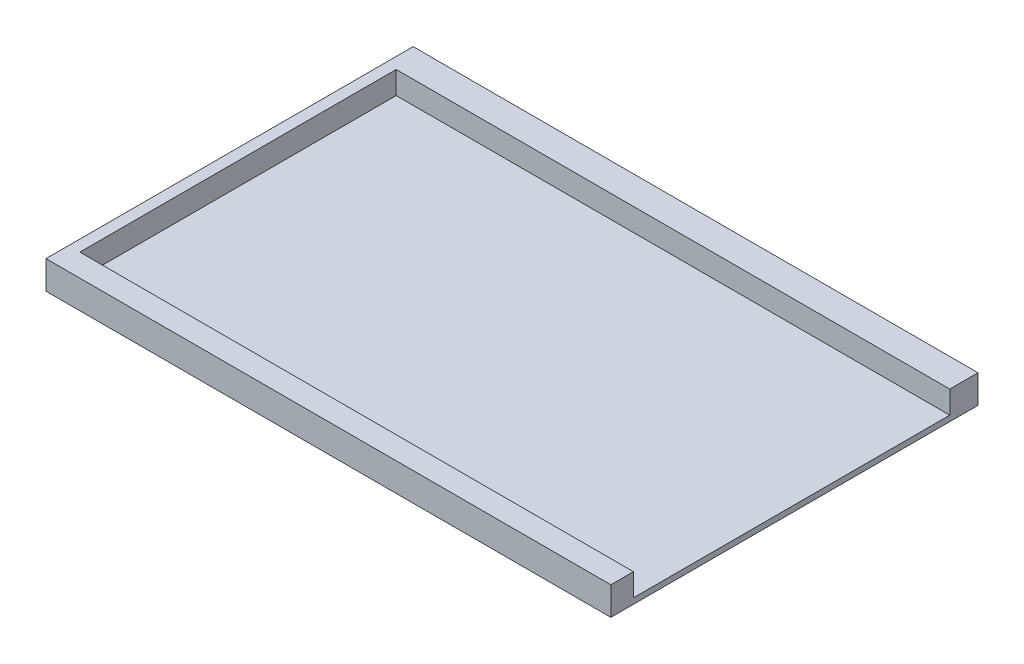
SolidWorks part; units mm, degrees
ref_plane "Front Plane" through (0, 0, 0) normal (0, 0, 1) x (1, 0, 0)
ref_plane "Top Plane" through (0, 0, 0) normal (0, 1, 0) x (1, 0, 0)
ref_plane "Right Plane" through (0, 0, 0) normal (1, 0, 0) x (0, 0, -1)
sketch "Sketch3" plane through (0, 0, 0) normal (0, 1, 0) x (1, 0, 0)
  line L1 (-50, -32.5) -> (50, -32.5)
  line L2 (-50, -32.5) -> (-50, 32.5)
  line L3 (-50, 32.5) -> (50, 32.5)
  line L4 (50, -32.5) -> (50, 32.5)
  line L5 (0, 32.5) -> (0, -32.5) construction
  line L6 (-50, 0) -> (50, 0) construction
  point P0 (0, 0)
  dimension "D1" = 100
  dimension "D2" = 65
extrude "Boss-Extrude2" add sketch "Sketch3" along normal blind 5
sketch "Sketch5" plane through (50, 0, 0) normal (1, 0, 0) x (0, 0, -1)
  line L0 (-32.5, 5) -> (32.5, 5) construction
  line L1 (-28.5, 1) -> (27.5, 1)
  line L2 (-28.5, 1) -> (-28.5, 5)
  line L3 (-28.5, 5) -> (27.5, 5)
  line L4 (27.5, 1) -> (27.5, 5)
  line L5 (-32.5, 0) -> (32.5, 0) construction
  line L6 (-32.5, 5) -> (-32.5, 0) construction
  line L7 (32.5, 5) -> (32.5, 0) construction
  dimension "D1" = 1
  dimension "D2" = 4
  dimension "D3" = 5
extrude "Cut-Extrude1" cut sketch "Sketch5" against normal blind 98
